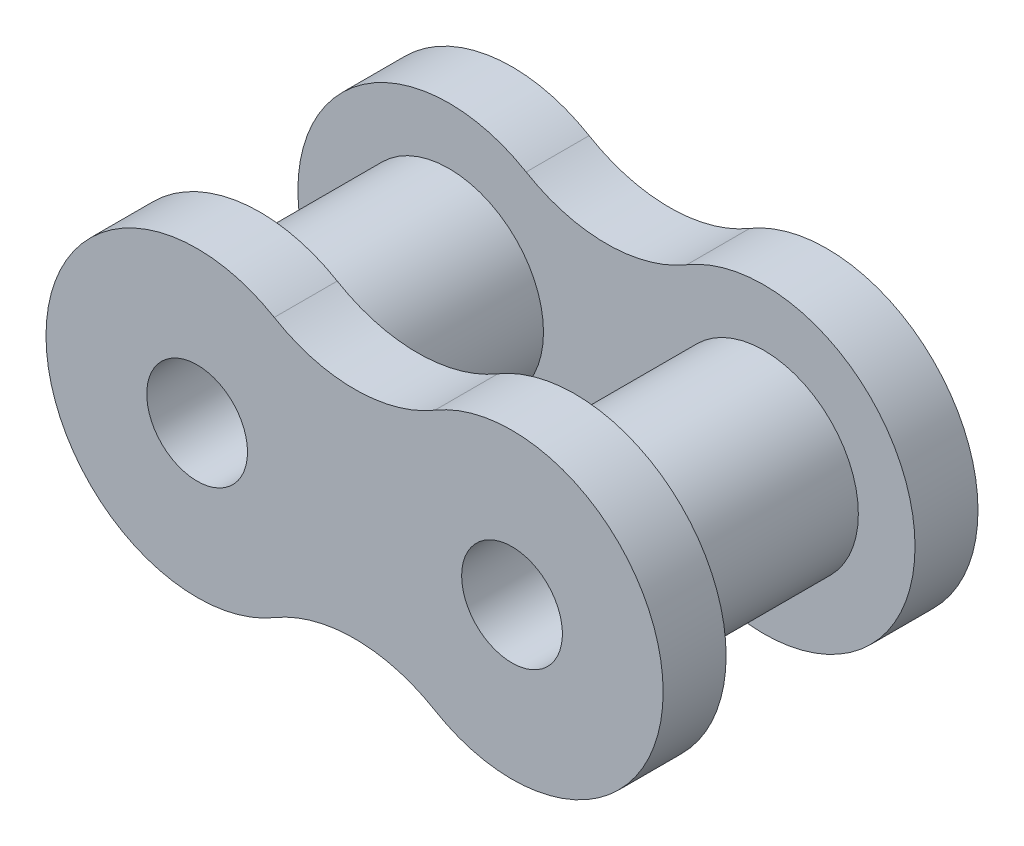
SolidWorks part; units mm, degrees
ref_plane "Front Plane" through (0, 0, 0) normal (0, 0, 1) x (1, 0, 0)
ref_plane "Top Plane" through (0, 0, 0) normal (0, 1, 0) x (1, 0, 0)
ref_plane "Right Plane" through (0, 0, 0) normal (1, 0, 0) x (0, 0, -1)
sketch "Sketch1" plane through (0, 0, 0) normal (0, 0, 1) x (1, 0, 0)
  line L0 (0, -1000.3258) -> (0, -0.1714) construction
  line L1 (-0.25, 0) -> (0, 0) construction
  line L2 (0, 0) -> (0, 1000.3142) construction
  arc A1 (-0.1276, 0.2064) -> (-0.1276, -0.2064) centre (-0.25, 0) ccw
  arc A2 (0.1276, 0.2064) -> (0.1276, -0.2064) centre (0.25, 0) cw
  circle A3 centre (-0.25, 0) radius 0.08
  circle A4 centre (0.25, 0) radius 0.08
  arc A5 (-0.1276, 0.2064) -> (0.1276, 0.2064) centre (0, 0.4214) ccw
  arc A6 (-0.1276, -0.2064) -> (0.1276, -0.2064) centre (0, -0.4214) cw
  point P13 (0, 0)
  point P14 (-0.0763, 0.1656)
  dimension "D1" = 0.48
  dimension "D3" = 0.16
  dimension "D4" = 0.25
  dimension "D2" = 0.25
extrude "Boss-Extrude1" add sketch "Sketch1" against normal blind 0.1
sketch "Sketch2" plane through (0, 0, 0) normal (0, 0, 1) x (1, 0, 0)
  line L0 (0, 0) -> (0, 0.1714) construction
  circle A0 centre (-0.25, 0) radius 0.15
  circle A1 centre (-0.25, 0) radius 0.08 construction
  circle A2 centre (-0.25, 0) radius 0.08
  arc A3 (-0.1276, 0.2064) -> (0.1276, 0.2064) centre (0, 0.4214) ccw construction
  circle A4 centre (0.25, 0) radius 0.08
  circle A5 centre (0.25, 0) radius 0.15
  dimension "D1" = 0.3
extrude "Boss-Extrude2" add sketch "Sketch2" along normal blind 0.3
ref_plane "Plane1" through (0, 0, 0.15) normal (0, 0, 1) x (1, 0, 0)
mirror "Mirror1" about plane through (0, 0, 0.15) normal (0, 0, 1) of "Boss-Extrude1"
